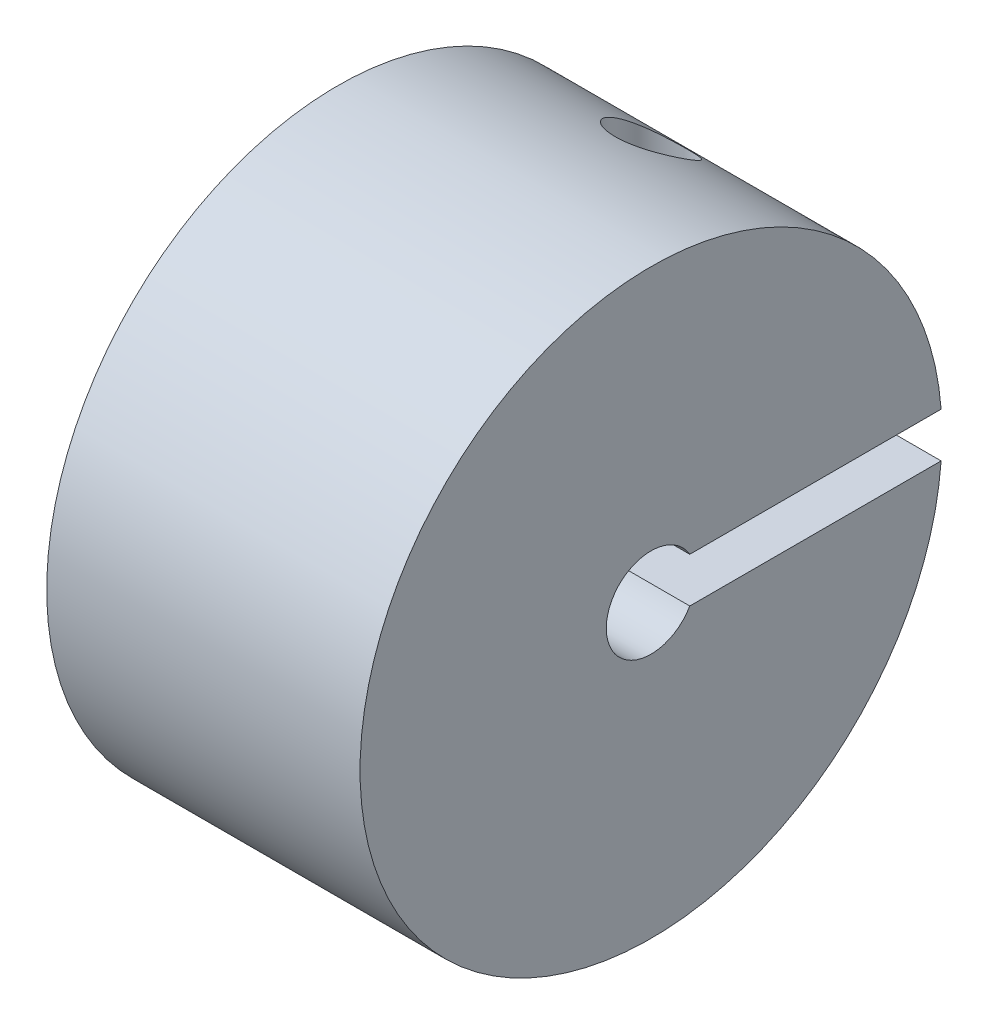
SolidWorks part; units mm, degrees
ref_plane "Front Plane" through (0, 0, 0) normal (0, 0, 1) x (1, 0, 0)
ref_plane "Top Plane" through (0, 0, 0) normal (0, 1, 0) x (1, 0, 0)
ref_plane "Right Plane" through (0, 0, 0) normal (1, 0, 0) x (0, 0, -1)
sketch "Sketch1" plane through (0, 0, 0) normal (1, 0, 0) x (0, 0, -1)
  circle A0 centre (0, 0) radius 6.5
  circle A1 centre (0, 0) radius 1
  dimension "D1" = 2
  dimension "D2" = 13
extrude "Boss-Extrude1" add sketch "Sketch1" along normal blind 7
sketch "Sketch2" plane through (0, 0, 0) normal (1, 0, 0) x (0, 0, -1)
  line L1 (0, 0.5) -> (6.5256, 0.5)
  line L2 (0, 0.5) -> (0, -0.5)
  line L3 (0, -0.5) -> (6.5256, -0.5)
  line L4 (6.5256, 0.5) -> (6.5256, -0.5)
  point P4 (6.5256, 0.6915)
  dimension "D1" = 1
extrude "Cut-Extrude2" cut sketch "Sketch2" along normal through all
sketch "Sketch3" plane through (0, 0, 0) normal (0, 1, 0) x (1, 0, 0)
  line L0 (3.5, -6.5) -> (3.5, 6.4807) construction
  line L1 (0, -6.5) -> (7, -6.5) construction
  line L2 (0, 6.4807) -> (7, 6.4807) construction
  circle A0 centre (3.5, 3.5) radius 1.25
  dimension "D1" = 2.5
  dimension "D2" = 3.5
extrude "Cut-Extrude3" cut sketch "Sketch3" against normal through all
sketch "Sketch4" plane through (0, 0, 0) normal (0, 1, 0) x (1, 0, 0)
  line L0 (3.5, -6.5) -> (3.5, 3.5) construction
  line L1 (0, -6.5) -> (7, -6.5) construction
  line L2 (1.4, 3.5) -> (1.4, 9.0142)
  line L3 (1.4, 9.0142) -> (5.6, 9.0142)
  line L4 (5.6, 9.0142) -> (5.6, 3.5)
  arc A0 (1.4, 3.5) -> (5.6, 3.5) centre (3.5, 3.5) ccw
  point P1 (5.5996, 3.4602)
  point P10 (4.9336, 9.0142)
  dimension "D1" = 4.2
  dimension "D2" = 3.5
extrude "Cut-Extrude5" cut sketch "Sketch4" against normal through all from offset 2 offset against normal yes
hole_wizard "M2 Tapped Hole2" positions "Sketch7" profile "Sketch8" tap size "M2" standard "ISO" end condition through all
sketch "Sketch7" plane through (0, 0.5, 0) normal (0, -1, 0) x (-1, 0, 0)
  point P0 (-3.5, 3.5)
sketch "Sketch8" plane through (3.5, 0.5, -3.5) normal (1, 0, 0) x (0, 0, -1)
  line L0 (0, 0) -> (0, 6)
  line L1 (0, 6) -> (0.8, 6)
  line L2 (0.8, 6) -> (0.8, 0)
  line L5 (0.8, 0) -> (0, 0)
  line L11 (0, -6.35) -> (0, 107.95) construction
  dimension "Thru Tap Drill Dia." = 1.6
  dimension "Thru Tap Drill Depth" = 6
cosmetic thread "Hole Thread2" parameters "D2"=2
